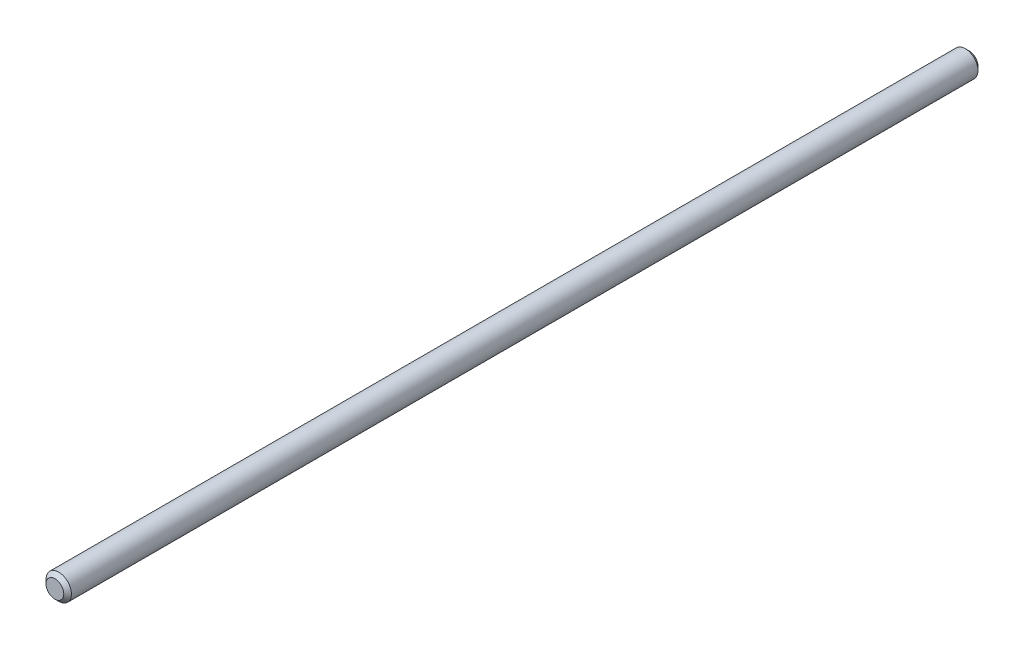
SolidWorks part; units mm, degrees
ref_plane "Front Plane" through (0, 0, 0) normal (0, 0, 1) x (1, 0, 0)
ref_plane "Top Plane" through (0, 0, 0) normal (0, 1, 0) x (1, 0, 0)
ref_plane "Right Plane" through (0, 0, 0) normal (1, 0, 0) x (0, 0, -1)
sketch "Sketch1" plane through (0, 0, 0) normal (0, 0, 1) x (1, 0, 0)
  circle A0 centre (0, 0) radius 2.5
  dimension "D1" = 5
extrude "Boss-Extrude1" add sketch "Sketch1" along normal blind 180
chamfer "Chamfer1" distance 0.75 angle 45 2 edges at (2.5, 0, 0) (2.5, 0, 180)
